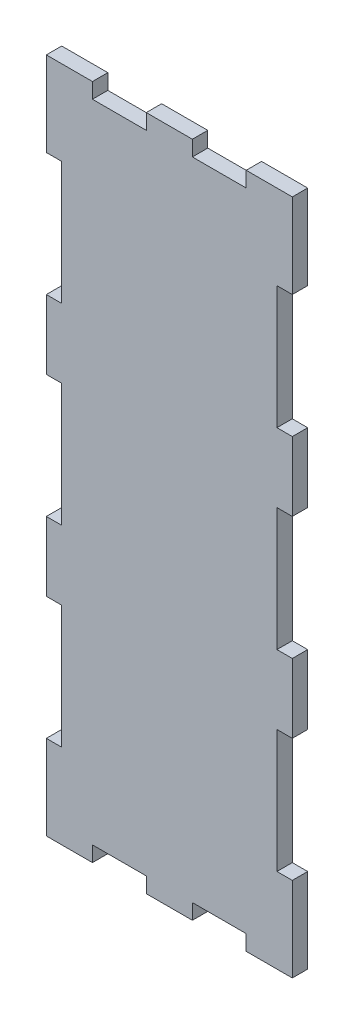
SolidWorks part; units mm, degrees
ref_plane "Front Plane" through (0, 0, 0) normal (0, 0, 1) x (1, 0, 0)
ref_plane "Top Plane" through (0, 0, 0) normal (0, 1, 0) x (1, 0, 0)
ref_plane "Right Plane" through (0, 0, 0) normal (1, 0, 0) x (0, 0, -1)
sketch "Sketch1" plane through (0, 0, 0) normal (0, 1, 0) x (1, 0, 0)
  line L1 (-28, 2) -> (28, 2)
  line L2 (-28, 2) -> (-28, -2)
  line L3 (-28, -2) -> (28, -2)
  line L4 (28, 2) -> (28, -2)
  line L5 (-28, 2) -> (28, -2) construction
  line L6 (-28, -2) -> (28, 2) construction
  point P0 (0, 0)
  dimension "D1" = 4
  dimension "D2" = 56
extrude "Boss-Extrude1" add sketch "Sketch1" along normal blind 168
sketch "Sketch2" plane through (0, 0, 2) normal (0, 0, 1) x (1, 0, 0)
  line L1 (-28, 0) -> (-32, 0)
  line L2 (-28, 0) -> (-28, 18)
  line L3 (-28, 18) -> (-32, 18)
  line L4 (-32, 0) -> (-32, 18)
  dimension "D1" = 4
  dimension "D2" = 18
extrude "Boss-Extrude3" add sketch "Sketch2" against normal through all contours L2 L1 L4 L3
pattern_linear "LPattern1" count 4 spacing 50 along (0, 1, 0) of "Boss-Extrude3"
mirror "Mirror1" about plane through (0, 0, 0) normal (1, 0, 0) of "LPattern1", "Boss-Extrude3"
sketch "Sketch3" plane through (0, 0, -2) normal (0, 0, -1) x (-1, 0, 0)
  line L0 (32, 0) -> (32, -4)
  line L1 (32, -4) -> (20, -4)
  line L2 (20, -4) -> (20, 0)
  line L3 (-32, 0) -> (32, 0) construction
  line L4 (20, 0) -> (32, 0)
  line L13 (-28, 84) -> (28, 84) construction
  line L14 (-28, 100) -> (-28, 68) construction
  line L15 (28, 100) -> (28, 68) construction
  line L28 (-6, -4) -> (-6, 0)
  line L29 (6, -4) -> (-6, -4)
  line L30 (-6, 0) -> (6, 0)
  line L31 (6, 0) -> (6, -4)
  line L32 (-32, -4) -> (-32, 0)
  line L33 (-20, -4) -> (-32, -4)
  line L34 (-32, 0) -> (-20, 0)
  line L35 (-20, 0) -> (-20, -4)
  dimension "D1" = 4
  dimension "D2" = 12
  dimension "D3" = 3
  dimension "D4" = 14
extrude "Boss-Extrude4" add sketch "Sketch3" against normal through all
ref_plane "Plane1" through (0, 84, 0) normal (0, -1, 0) x (-1, 0, 0)
mirror "Mirror2" about plane through (0, 84, 0) normal (0, -1, 0) of "Boss-Extrude4"
